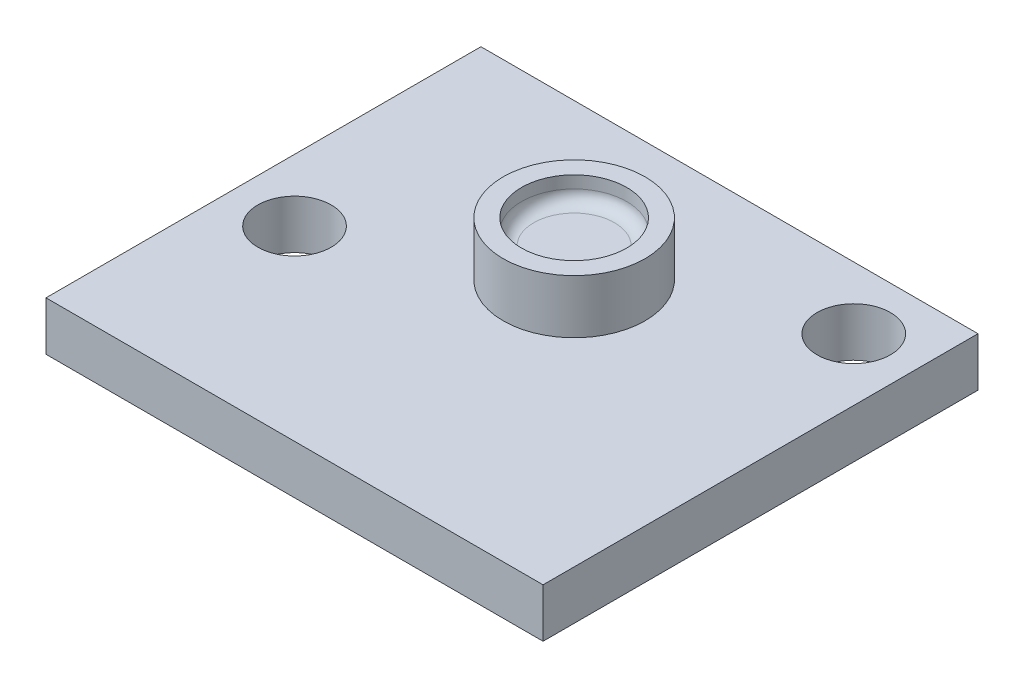
SolidWorks part; units mm, degrees
ref_plane "Front Plane" through (0, 0, 0) normal (0, 0, 1) x (1, 0, 0)
ref_plane "Top Plane" through (0, 0, 0) normal (0, 1, 0) x (1, 0, 0)
ref_plane "Right Plane" through (0, 0, 0) normal (1, 0, 0) x (0, 0, -1)
sketch "Sketch2" plane through (0, 0, 0) normal (0, 1, 0) x (1, 0, 0)
  line L1 (-10.16, -8.89) -> (10.16, -8.89)
  line L2 (-10.16, -8.89) -> (-10.16, 8.89)
  line L3 (-10.16, 8.89) -> (10.16, 8.89)
  line L4 (10.16, -8.89) -> (10.16, 8.89)
  line L5 (-10.16, -8.89) -> (10.16, 8.89) construction
  line L6 (-10.16, 8.89) -> (10.16, -8.89) construction
  line L7 (-10.16, -8.89) -> (-7.62, -8.89)
  line L8 (-10.16, -8.89) -> (-10.16, -1.27)
  line L9 (-10.16, -1.27) -> (-7.62, -1.27)
  line L10 (-7.62, -8.89) -> (-7.62, -1.27)
  line L11 (-10.16, -8.89) -> (0, -8.89)
  line L12 (-10.16, -8.89) -> (-10.16, 2.54)
  line L13 (-10.16, 2.54) -> (0, 2.54)
  line L14 (0, -8.89) -> (0, 2.54)
  line L15 (-10.16, -8.89) -> (7.62, -8.89)
  line L16 (-10.16, -8.89) -> (-10.16, 6.35)
  line L17 (-10.16, 6.35) -> (7.62, 6.35)
  line L18 (7.62, -8.89) -> (7.62, 6.35)
  circle A0 centre (-7.62, -1.27) radius 1.5
  circle A1 centre (0, 2.54) radius 2.9
  circle A2 centre (7.62, 6.35) radius 1.5
  point P0 (0, 0)
  dimension "D5" = 3
  dimension "D10" = 5.8
  dimension "D11" = 3
  dimension "D1" = 20.32
  dimension "D2" = 17.78
  dimension "D3" = 2.54
  dimension "D4" = 7.62
  dimension "D6" = 10.16
  dimension "D7" = 11.43
  dimension "D8" = 17.78
  dimension "D9" = 15.24
extrude "Boss-Extrude1" add sketch "Sketch2" along normal blind 2 contours A2 L17 L2 L13 A1 L14 L1 L18 | A1 L13 L2 L9 A0 L10 L1 L14 | A0 L9 L2 L1 L10
sketch "Sketch3" plane through (0, 2, 0) normal (0, 1, 0) x (1, 0, 0)
  circle A0 centre (0, 2.54) radius 2.9
  dimension "D1" = 5.8
extrude "Boss-Extrude2" add sketch "Sketch3" along normal blind 2.2
sketch "Sketch4" plane through (0, 4.2, 0) normal (0, 1, 0) x (1, 0, 0)
  circle A0 centre (0, 2.54) radius 2.15
  dimension "D1" = 4.3
extrude "Cut-Extrude1" cut sketch "Sketch4" against normal blind 1
fillet "Fillet2" radius 0.5 1 edges at (0, 3.2, -0.39)
